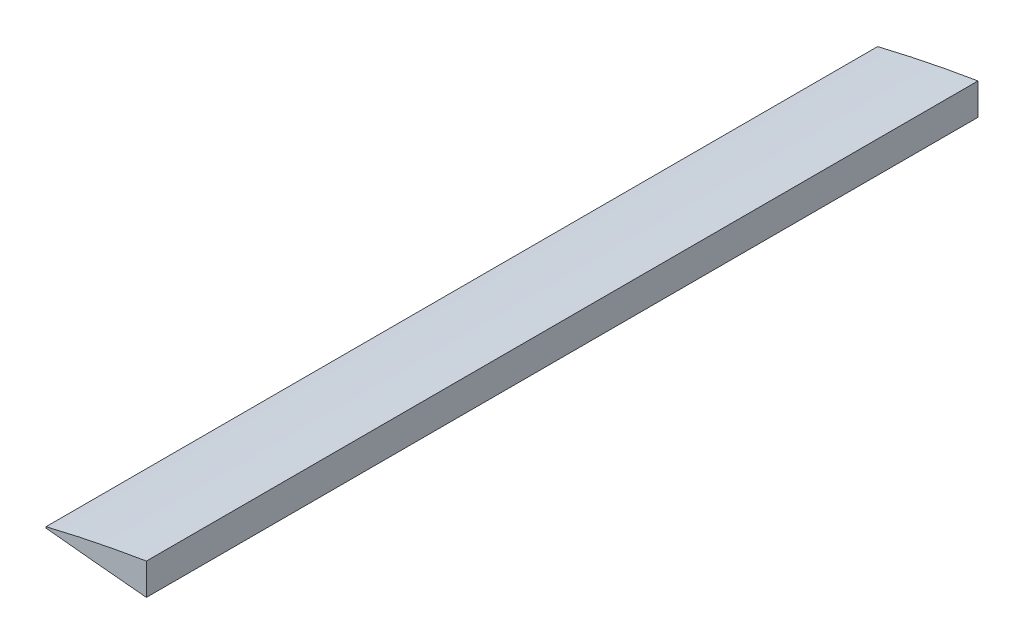
SolidWorks part; units mm, degrees
ref_plane "Front Plane" through (0, 0, 0) normal (0, 0, 1) x (1, 0, 0)
ref_plane "Top Plane" through (0, 0, 0) normal (0, 1, 0) x (1, 0, 0)
ref_plane "Right Plane" through (0, 0, 0) normal (1, 0, 0) x (0, 0, -1)
sketch "Sketch1" plane through (0, 0, 0) normal (0, 0, 1) x (1, 0, 0)
  line L0 (-210.2902, 15.5058) -> (-210.2902, -7.6848)
  line L1 (-284.176, 0.4539) -> (-284.176, -0.4466)
  spline S0 degree 3 poles (-210.2902, 15.5058) (-212.4482, 15.1479) (-217.6988, 14.2771) (-225.8551, 12.8241) (-234.5739, 11.2048) (-242.7164, 9.62) (-250.2347, 8.0968) (-257.084, 6.6572) (-263.2241, 5.3239) (-268.6191, 4.1181) (-273.2376, 3.0598) (-277.0529, 2.1669) (-280.0432, 1.4552) (-282.1913, 0.9372) (-283.4751, 0.6251) (-284.0416, 0.4867) (-284.176, 0.4539) knots 0 0 0 0 0.087007 0.211705 0.329527 0.439741 0.541661 0.634652 0.718135 0.791585 0.85454 0.906603 0.947445 0.976805 0.994497 1 1 1 1
  spline S1 degree 3 poles (-210.2902, -7.6848) (-212.1587, -7.5154) (-217.125, -7.0652) (-225.0196, -6.3317) (-233.7877, -5.5057) (-241.996, -4.7193) (-249.5923, -3.9801) (-256.5279, -3.2948) (-262.7581, -2.6701) (-268.2426, -2.1118) (-272.9458, -1.6282) (-276.8367, -1.2191) (-279.8905, -0.906) (-282.085, -0.6533) (-283.41, -0.5467) (-284.0076, -0.446) (-284.1661, -0.4466) (-284.176, -0.4466) knots 0 0 0 0 0.075811 0.201508 0.320388 0.431695 0.534719 0.628797 0.713321 0.78774 0.851567 0.90438 0.945827 0.975633 0.993597 0.999599 1 1 1 1
extrude "Boss-Extrude1" add sketch "Sketch1" along normal blind 612
ref_plane "Plane1" through (0, 0, 83.9) normal (0, 0, 1) x (1, 0, 0)
sketch "Sketch2" plane through (0, 0, 83.9) normal (0, 0, 1) x (1, 0, 0)
  line L0 (-233.632, -8.192) -> (-212.632, -8.192)
  line L1 (-212.632, -8.192) -> (-212.632, 3.308)
  line L2 (-212.632, 3.308) -> (-233.632, 3.308)
  line L3 (-233.632, 3.308) -> (-233.632, -8.192)
extrude "Cut-Extrude1" cut sketch "Sketch2" along normal blind 13
